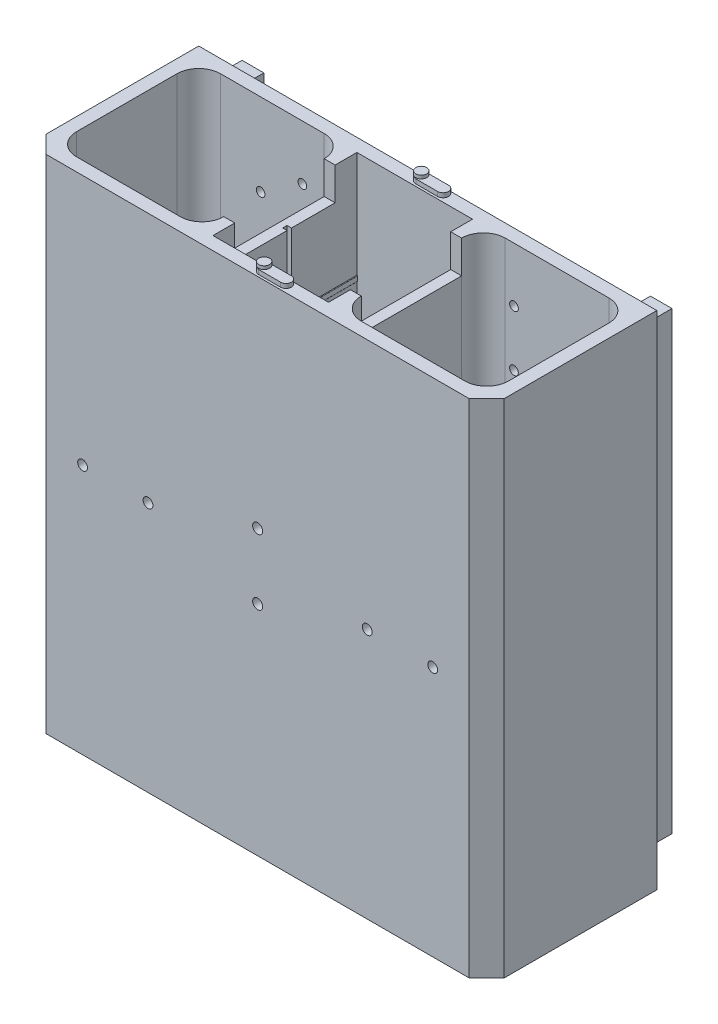
SolidWorks part; units mm, degrees
ref_plane "前视基准面" through (0, 0, 0) normal (0, 0, 1) x (1, 0, 0)
ref_plane "上视基准面" through (0, 0, 0) normal (0, 1, 0) x (1, 0, 0)
ref_plane "右视基准面" through (0, 0, 0) normal (1, 0, 0) x (0, 0, -1)
other "Configuration Table"
sketch "草图1" plane through (0, 0, 0) normal (0, 0, 1) x (1, 0, 0)
  line L1 (0, 0) -> (210, 0)
  line L2 (0, 0) -> (0, 230)
  line L3 (0, 230) -> (210, 230)
  line L4 (210, 0) -> (210, 230)
  line L5 (0, 0) -> (210, 230) construction
  line L6 (0, 230) -> (210, 0) construction
  line L7 (0, 230) -> (26, 230)
  line L8 (0, 230) -> (0, 0)
  line L9 (0, 0) -> (26, 0)
  point P4 (105, 115)
  point P8 (13, 115)
  dimension "D1" = 230
  dimension "D2" = 210
extrude "凸台-拉伸1" add sketch "草图1" along normal blind 6 contours L1 L4 L3 L2
sketch "草图2" plane through (0, 0, 0) normal (0, 0, -1) x (-1, 0, 0)
  line L0 (0, 230) -> (-210, 230) construction
  line L1 (0, 0) -> (-210, 0) construction
  line L2 (-210, 230) -> (-184, 230)
  line L3 (-210, 230) -> (-210, 0)
  line L4 (-210, 0) -> (-184, 0)
  line L5 (-184, 230) -> (-184, 0) construction
  line L6 (-210, 230) -> (-184, 0) construction
  line L7 (-210, 0) -> (-184, 230) construction
  line L9 (0, 230) -> (-20, 230)
  line L10 (0, 230) -> (0, 0)
  line L11 (0, 0) -> (-20, 0)
  line L13 (0, 230) -> (-20, 0) construction
  line L14 (0, 0) -> (-20, 230) construction
  line L15 (-201.925, 219.25) -> (-192.075, 219.25)
  line L16 (-201.925, 219.25) -> (-201.925, 10.75)
  line L17 (-201.925, 10.75) -> (-192.075, 10.75)
  line L18 (-192.075, 219.25) -> (-192.075, 10.75)
  line L19 (-201.925, 219.25) -> (-192.075, 10.75) construction
  line L20 (-201.925, 10.75) -> (-192.075, 219.25) construction
  line L21 (-14.85, 219.25) -> (-4.85, 219.25)
  line L22 (-14.85, 219.25) -> (-14.85, 10.75)
  line L23 (-14.85, 10.75) -> (-4.85, 10.75)
  line L24 (-4.85, 219.25) -> (-4.85, 10.75)
  line L25 (-14.85, 219.25) -> (-4.85, 10.75) construction
  line L26 (-14.85, 10.75) -> (-4.85, 219.25) construction
  point P6 (-197, 115)
  point P18 (-197, 115)
  point P23 (-9.85, 115)
  dimension "D1" = 26
  dimension "D2" = 20
  dimension "D3" = 208.5
  dimension "D4" = 9.85
  dimension "D5" = 13
  dimension "D6" = 115
  dimension "D7" = 208.5
  dimension "D8" = 115
  dimension "D9" = 9.85
  dimension "D10" = 10
extrude "凸台-拉伸3" add sketch "草图2" along normal blind 15 contours L18 L15 L16 L17 | L24 L21 L22 L23
sketch "草图3" plane through (0, 0, 0) normal (0, 0, -1) x (-1, 0, 0)
  line L0 (0, 0) -> (-210, 0) construction
  line L1 (-210, 230) -> (-184, 230)
  line L2 (-210, 230) -> (-210, 0)
  line L3 (-210, 0) -> (-184, 0)
  line L4 (-184, 230) -> (-184, 0)
  line L5 (-210, 230) -> (-184, 0) construction
  line L6 (-210, 0) -> (-184, 230) construction
  line L7 (-210, 115) -> (119.2636, 115) construction
  line L8 (0, 230) -> (-20, 230)
  line L9 (0, 230) -> (0, 0)
  line L10 (0, 0) -> (-20, 0)
  line L11 (-20, 230) -> (-20, 0)
  line L12 (0, 230) -> (-20, 0) construction
  line L13 (0, 0) -> (-20, 230) construction
  line L14 (-105, 230) -> (-105, 0) construction
  circle A0 centre (-169.6426, 192.25) radius 2
  circle A1 centre (-150.5, 205) radius 2
  circle A2 centre (-150.5, 179.5) radius 2
  circle A3 centre (-150.5, 50.5) radius 2
  circle A4 centre (-150.5, 25) radius 2
  circle A5 centre (-169.6426, 37.75) radius 2
  circle A6 centre (-34.3574, 192.25) radius 2
  circle A7 centre (-53.5, 205) radius 2
  circle A8 centre (-53.5, 179.5) radius 2
  circle A9 centre (-53.5, 50.5) radius 2
  circle A10 centre (-53.5, 25) radius 2
  circle A11 centre (-34.3574, 37.75) radius 2
  point P4 (-197, 115)
  point P12 (-10, 115)
  dimension "D8" = 4
  dimension "D9" = 4
  dimension "D10" = 4
  dimension "D12" = 4
  dimension "D13" = 4
  dimension "D14" = 4
  dimension "D1" = 26
  dimension "D2" = 20
  dimension "D3" = 25.5
  dimension "D4" = 23
  dimension "D5" = 23
  dimension "D6" = 33.5
  dimension "D7" = 33.5
  dimension "D11" = 90
  dimension "D15" = 25.5
  dimension "D16" = 23
  dimension "D17" = 23
  dimension "D18" = 33.5
  dimension "D19" = 33.5
  dimension "D20" = 90
extrude "切除-拉伸1" cut sketch "草图3" against normal blind 10 contours A10 | A11 | A9 | A6 | A8 | A7 | A1 | A2 | A0 | A4 | A3 | A5
chamfer "倒角1" [suppressed] distance 10 angle 45
sketch "草图5" [suppressed] plane through (0, 0, 0) normal (0, 0, -1) x (-1, 0, 0)
  line L0 (-172.5, 115) -> (-135, 115) construction
  line L1 (-10, 230) -> (-200, 230) construction
  line L2 (-210, 10) -> (-210, 220) construction
  line L5 (-210, 220) -> (-210, 0)
  line L8 (-75, 115) -> (-37.5, 115) construction
  line L9 (-210, 0) -> (-184, 220) construction
  line L10 (0, 10) -> (0, 220) construction
  circle A0 centre (-172.5, 115) radius 2.5
  circle A1 centre (-135, 115) radius 2.5
  circle A2 centre (-75, 115) radius 2.5
  circle A3 centre (-37.5, 115) radius 2.5
  point P12 (-197, 110)
  dimension "D3" = 5
  dimension "D4" = 5
  dimension "D8" = 5
  dimension "D9" = 5
  dimension "D1" = 37.5
  dimension "D2" = 115
  dimension "D5" = 75
  dimension "D6" = 26
  dimension "D7" = 37.5
  dimension "D10" = 115
  dimension "D11" = 75
extrude "切除-拉伸2" [suppressed] cut sketch "草图5" against normal blind 10 contours A0 | A1 | A3 | A2
sketch "草图6" plane through (0, 0, 6) normal (0, 0, 1) x (1, 0, 0)
  line L0 (105, 230) -> (105, 0) construction
  line L3 (0, 115) -> (210, 115) construction
  line L6 (86.25, 115) -> (123.75, 115) construction
  line L7 (105, 133.75) -> (105, 96.25) construction
  circle A2 centre (105, 133.75) radius 2.5
  circle A3 centre (105, 96.25) radius 2.5
  point P7 (105, 115)
  point P11 (105, 115)
  dimension "D1" = 37.5
  dimension "D2" = 5
  dimension "D3" = 5
extrude "切除-拉伸3" [suppressed] cut sketch "草图6" against normal blind 10
sketch "草图7" [suppressed] plane through (0, 0, 18) normal (0, 0, 1) x (1, 0, 0)
  line L0 (0, 0) -> (210, 0) construction
  line L1 (0, 230) -> (6, 230)
  line L2 (0, 230) -> (0, 0)
  line L3 (0, 0) -> (6, 0)
  line L4 (6, 230) -> (6, 0)
  line L5 (0, 230) -> (6, 0) construction
  line L6 (0, 0) -> (6, 230) construction
  point P4 (3, 115)
  dimension "D1" = 6
extrude "凸台-拉伸4" [suppressed] add sketch "草图7" along normal blind 55
sketch "草图8" [suppressed] plane through (0, 0, 18) normal (0, 0, 1) x (1, 0, 0)
  line L0 (0, 0) -> (210, 0) construction
  line L1 (210, 230) -> (200.2731, 230)
  line L2 (210, 230) -> (210, 0)
  line L3 (210, 0) -> (200.2731, 0)
  line L4 (200.2731, 230) -> (200.2731, 0)
  line L5 (210, 230) -> (200.2731, 0) construction
  line L6 (210, 0) -> (200.2731, 230) construction
  point P4 (205.1365, 115)
  dimension "D1" = 9.7269
sketch "草图17" plane through (0, 0, 6) normal (0, 0, 1) x (1, 0, 0)
  line L0 (0, 0) -> (210, 0) construction
  line L1 (0, 230) -> (6, 230)
  line L2 (0, 230) -> (0, 0)
  line L3 (0, 0) -> (6, 0)
  line L4 (6, 230) -> (6, 0)
  line L5 (0, 230) -> (6, 0) construction
  line L6 (0, 0) -> (6, 230) construction
  line L8 (210, 230) -> (204, 230)
  line L9 (210, 230) -> (210, 0)
  line L10 (210, 0) -> (204, 0)
  line L11 (204, 230) -> (204, 0)
  line L12 (210, 230) -> (204, 0) construction
  line L13 (210, 0) -> (204, 230) construction
  point P4 (3, 115)
  point P12 (207, 115)
  dimension "D1" = 6
  dimension "D2" = 6
extrude "凸台-拉伸9" add sketch "草图17" along normal blind 66
ref_plane "基准面2" through (0, 0, 72) normal (0, 0, 1) x (1, 0, 0)
sketch "草图18" plane through (0, 0, 72) normal (0, 0, 1) x (1, 0, 0)
  line L0 (210, 230) -> (204, 230) construction
  line L1 (210, 0) -> (210, 230) construction
  line L2 (204, 0) -> (210, 0) construction
  line L3 (6, 0) -> (204, 0) construction
  line L4 (0, 0) -> (6, 0) construction
  line L5 (0, 230) -> (0, 0) construction
  line L6 (6, 230) -> (0, 230) construction
  line L7 (6, 230) -> (204, 230) construction
  line L8 (210, 230) -> (204, 230)
  line L9 (210, 0) -> (210, 230)
  line L10 (204, 0) -> (210, 0)
  line L11 (6, 0) -> (204, 0)
  line L12 (0, 0) -> (6, 0)
  line L13 (0, 230) -> (0, 0)
  line L14 (6, 230) -> (0, 230)
  line L15 (6, 230) -> (204, 230)
extrude "凸台-拉伸10" add sketch "草图18" along normal blind 6
chamfer "倒角3" distance 8 angle 45 2 edges at (0, 115, 78) (210, 115, 78)
sketch "草图19" plane through (0, 0, 72) normal (0, 0, -1) x (-1, 0, 0)
  line L0 (-105, 230) -> (-105, 0) construction
  line L2 (-131.5, 230) -> (-136.5, 230)
  line L3 (0, 230) -> (-210, 230) construction
  line L4 (0, 0) -> (-210, 0) construction
  line L5 (-131.5, 230) -> (-131.5, 0)
  line L6 (-131.5, 230) -> (-78.5, 230)
  line L7 (-131.5, 230) -> (-131.5, 0)
  line L8 (-131.5, 0) -> (-78.5, 0)
  line L9 (-78.5, 230) -> (-78.5, 0)
  line L10 (-131.5, 230) -> (-78.5, 0) construction
  line L11 (-131.5, 0) -> (-78.5, 230) construction
  line L12 (-131.5, 0) -> (-136.5, 0)
  line L13 (-136.5, 230) -> (-136.5, 0)
  line L14 (-131.5, 230) -> (-136.5, 0) construction
  line L15 (-131.5, 0) -> (-136.5, 230) construction
  line L16 (-78.5, 230) -> (-73.5, 230)
  line L17 (-78.5, 230) -> (-78.5, 0)
  line L18 (-78.5, 0) -> (-73.5, 0)
  line L19 (-73.5, 230) -> (-73.5, 0)
  line L20 (-78.5, 230) -> (-73.5, 0) construction
  line L21 (-78.5, 0) -> (-73.5, 230) construction
  point P10 (-105, 115)
  point P13 (-134, 115)
  point P16 (-76, 115)
  dimension "D1" = 53
  dimension "D2" = 0
  dimension "D3" = 5
  dimension "D4" = 5
extrude "凸台-拉伸11" add sketch "草图19" along normal blind 66 contours L19 L7 L9 L4 | L7 L13 L4 L5
fillet "圆角4" radius 10 8 edges at (136.5, 115, 72) (136.5, 115, 6) (204, 115, 6) (204, 115, 72) (73.5, 115, 6) (73.5, 115, 72) (6, 115, 6) (6, 115, 72)
sketch "草图21" plane through (0, 0, 72) normal (0, 0, 1) x (1, 0, 0)
  line L0 (8, 115) -> (202, 115) construction
  line L1 (8, 230) -> (8, 0) construction
  line L2 (202, 0) -> (202, 230) construction
  line L3 (105, 230) -> (105, 0) construction
  line L4 (202, 230) -> (8, 230) construction
  line L5 (8, 0) -> (202, 0) construction
  line L6 (105, 130) -> (105, 100) construction
  circle A0 centre (105, 130) radius 2.3
  circle A1 centre (105, 100) radius 2.3
  point P14 (105, 115)
  dimension "D3" = 4.6
  dimension "D4" = 4.6
  dimension "D1" = 0
  dimension "D2" = 30
extrude "切除-拉伸9" cut sketch "草图21" along normal blind 6 contours A1 | A0
sketch "草图23" plane through (78.5, 0, 0) normal (1, 0, 0) x (0, 0, -1)
  line L0 (-6, 80) -> (-70, 80)
  line L1 (-6, 230) -> (-70, 230) construction
  line L2 (-6, 230) -> (-6, 0) construction
  line L3 (-6, 0) -> (-70, 0) construction
  line L4 (-70, 230) -> (-70, 0) construction
  line L5 (-6, 230) -> (-70, 0) construction
  line L6 (-6, 0) -> (-70, 230) construction
  line L7 (-6, 230) -> (-70, 230)
  line L8 (-6, 230) -> (-6, 40)
  line L9 (-6, 40) -> (-70, 40)
  line L10 (-70, 230) -> (-70, 40)
  line L11 (-6, 230) -> (-70, 40) construction
  line L12 (-6, 40) -> (-70, 230) construction
  point P4 (-38, 115)
  point P9 (-38, 135)
  dimension "D1" = 190
  dimension "D2" = 40
sketch "草图24" plane through (0, 0, 6) normal (0, 0, 1) x (1, 0, 0)
  line L0 (78.5, 80.5) -> (78.5, 79.5) construction
  line L1 (78.5, 230) -> (78.5, 40) construction
  line L2 (80, 80.5) -> (80, 79.5)
  line L4 (78.5, 82) -> (78.5, 78)
  arc A0 (80, 80.5) -> (78.5, 82) centre (78.5, 80.5) ccw
  arc A1 (78.5, 78) -> (80, 79.5) centre (78.5, 79.5) ccw
  point P0 (78.5, 80)
  point P6 (78.5, 80)
  dimension "D3" = 1.5
  dimension "D4" = 1.5
  dimension "D1" = 0
  dimension "D2" = 1
extrude "凸台-拉伸12" [suppressed] add sketch "草图24" along normal blind 66
ref_plane "基准面3" through (105, 0, 0) normal (-1, 0, 0) x (0, 0, 1)
mirror "镜向1" [suppressed] about plane through (105, 0, 0) normal (-1, 0, 0)
sketch "草图25" plane through (0, 0, 72) normal (0, 0, -1) x (-1, 0, 0)
  line L8 (-131.5, 230) -> (-131.5, 0)
  line L11 (-131.5, 0) -> (-78.5, 0)
  line L12 (-78.5, 0) -> (-78.5, 230)
  line L15 (-78.5, 230) -> (-131.5, 230)
  line L16 (-131.5, 230) -> (-131.5, 0)
  line L19 (-131.5, 0) -> (-78.5, 0)
  line L20 (-78.5, 0) -> (-78.5, 230)
  line L23 (-78.5, 230) -> (-131.5, 230)
  dimension "D1" = 0
sketch "草图26" plane through (0, 0, 72) normal (0, 0, -1) x (-1, 0, 0)
  line L0 (-131.5, 181) -> (-131.5, 179) construction
  line L1 (-131.5, 230) -> (-131.5, 0) construction
  line L2 (-131.26, 181) -> (-131.26, 179)
  line L3 (-131.74, 181) -> (-131.74, 179)
  line L4 (-78.5, 230) -> (-131.5, 230) construction
  line L5 (-131.5, 230) -> (-131.5, 0) construction
  line L6 (-78.5, 230) -> (-131.5, 230) construction
  line L7 (-131.5, 22.5) -> (-131.5, 20.5) construction
  line L8 (-131.26, 22.5) -> (-131.26, 20.5)
  line L9 (-131.74, 22.5) -> (-131.74, 20.5)
  arc A0 (-131.26, 181) -> (-131.74, 181) centre (-131.5, 181) ccw
  arc A1 (-131.74, 179) -> (-131.26, 179) centre (-131.5, 179) ccw
  arc A2 (-131.26, 22.5) -> (-131.74, 22.5) centre (-131.5, 22.5) ccw
  arc A3 (-131.74, 20.5) -> (-131.26, 20.5) centre (-131.5, 20.5) ccw
  point P4 (-131.5, 180)
  point P14 (-131.5, 21.5)
  dimension "D1" = 0.24
  dimension "D2" = 2
  dimension "D3" = 50
  dimension "D4" = 2
extrude "凸台-拉伸13" add sketch "草图26" along normal blind 66
mirror "镜向2" about plane through (105, 0, 0) normal (-1, 0, 0) of "凸台-拉伸13"
sketch "草图28" plane through (0, 0, 72) normal (0, 0, -1) x (-1, 0, 0)
  line L0 (-78.5, 230) -> (-131.5, 230) construction
  line L1 (-78.5, 230) -> (-131.5, 230) construction
  line L2 (-131.5, 230) -> (-131.5, 0) construction
  line L3 (-131.5, 11.46) -> (-78.5, 11.46)
  line L4 (-131.5, 11.46) -> (-131.5, 8.46)
  line L5 (-131.5, 8.46) -> (-78.5, 8.46)
  line L6 (-78.5, 11.46) -> (-78.5, 8.46)
  line L7 (-131.5, 11.46) -> (-78.5, 8.46) construction
  line L8 (-131.5, 8.46) -> (-78.5, 11.46) construction
  line L9 (-78.5, 230) -> (-78.5, 0) construction
  point P6 (-105, 9.96)
  point P11 (-78.5, 20.2624)
  dimension "D1" = 218.54
  dimension "D2" = 3
extrude "凸台-拉伸14" add sketch "草图28" along normal blind 66
sketch "草图30" plane through (0, 230, 0) normal (0, 1, 0) x (1, 0, 0)
  line L0 (78.5, -6) -> (131.5, -6) construction
  line L1 (78.5, -6) -> (131.5, -6) construction
  line L2 (78.5, -6) -> (78.5, -70) construction
  line L3 (78.5, -36) -> (76.5, -36)
  line L4 (78.5, -36) -> (78.5, -38)
  line L5 (78.5, -38) -> (76.5, -38)
  line L6 (76.5, -36) -> (76.5, -38)
  line L7 (78.5, -36) -> (76.5, -38) construction
  line L8 (78.5, -38) -> (76.5, -36) construction
  point P6 (77.5, -37)
  dimension "D1" = 2
  dimension "D2" = 30
  dimension "D3" = 2
extrude "切除-拉伸10" cut sketch "草图30" against normal blind 35
sketch "草图31" plane through (0, 8.46, 0) normal (0, -1, 0) x (1, 0, 0)
  line L0 (105, 72) -> (105, 6) construction
  line L1 (105, 16.2) -> (117.5, 16.2) construction
  line L2 (98, 23.2) -> (112, 23.2)
  line L3 (98, 23.2) -> (98, 9.2)
  line L4 (131.5, 72) -> (78.5, 72)
  line L5 (78.5, 72) -> (78.5, 6)
  line L6 (78.5, 6) -> (131.5, 6)
  line L7 (131.5, 6) -> (131.5, 72)
  line L8 (131.5, 72) -> (78.5, 72) construction
  line L9 (78.5, 72) -> (78.5, 6) construction
  line L10 (78.5, 6) -> (131.5, 6) construction
  line L11 (131.5, 6) -> (131.5, 72) construction
  line L12 (98, 9.2) -> (112, 9.2)
  line L13 (112, 23.2) -> (112, 9.2)
  line L14 (98, 23.2) -> (112, 9.2) construction
  line L15 (98, 9.2) -> (112, 23.2) construction
  circle A0 centre (92.7, 16.2) radius 1.35
  circle A1 centre (117.3, 16.2) radius 1.35
  point P10 (105, 16.2)
  dimension "D8" = 2.7
  dimension "D9" = 2.7
  dimension "D2" = 14
  dimension "D3" = 14
  dimension "D4" = 12.3
  dimension "D5" = 12.3
  dimension "D6" = 3.2
  dimension "D7" = 0
  dimension "D1" = 0
extrude "切除-拉伸11" cut sketch "草图31" against normal through all
sketch "草图32" plane through (0, 0, 6) normal (0, 0, 1) x (1, 0, 0)
  line L0 (131.5, 8.46) -> (78.5, 8.46) construction
  line L1 (119.5, 8.46) -> (131.5, 8.46)
  line L2 (119.5, 8.46) -> (119.5, -1.54)
  line L3 (119.5, -1.54) -> (131.5, -1.54)
  line L4 (131.5, 8.46) -> (131.5, -1.54)
  line L5 (119.5, 8.46) -> (131.5, -1.54) construction
  line L6 (119.5, -1.54) -> (131.5, 8.46) construction
  line L7 (131.5, 8.46) -> (78.5, 8.46) construction
  line L8 (131.5, 8.46) -> (131.5, 0) construction
  line L9 (131.5, 8.46) -> (131.5, 0) construction
  line L10 (78.5, 0) -> (131.5, 0) construction
  line L11 (78.5, 0) -> (131.5, 0) construction
  point P4 (125.5, 3.46)
  dimension "D1" = 10
  dimension "D2" = 0
  dimension "D3" = 0
  dimension "D4" = 12
extrude "切除-拉伸12" [suppressed] cut sketch "草图32" against normal through all
sketch "草图33" [suppressed] plane through (131.5, 0, 0) normal (-1, 0, 0) x (0, 0, 1)
  line L0 (0, 8.46) -> (72, 8.46) construction
  line L1 (30, 8.46) -> (50, 8.46)
  line L2 (30, 8.46) -> (30, 0)
  line L3 (30, 0) -> (50, 0)
  line L4 (50, 8.46) -> (50, 0)
  line L5 (30, 8.46) -> (50, 0) construction
  line L6 (30, 0) -> (50, 8.46) construction
  line L7 (0, 0) -> (72, 0) construction
  line L8 (0, 0) -> (0, 8.46) construction
  point P4 (40, 4.23)
  point P9 (30, 4.23)
  dimension "D1" = 20
  dimension "D2" = 30
extrude "切除-拉伸13" [suppressed] cut sketch "草图33" against normal up to next
sketch "草图34" plane through (0, 0, 72) normal (0, 0, -1) x (-1, 0, 0)
  line L0 (-170.25, 230) -> (-170.25, 0) construction
  line L1 (-194, 115) -> (-146.5, 115) construction
  line L2 (-185.25, 115) -> (-155.25, 115)
  line L4 (-194, 0) -> (-146.5, 0)
  line L19 (-194, 0) -> (-146.5, 0)
  line L23 (-146.5, 0) -> (-146.5, 230)
  line L25 (-146.5, 0) -> (-146.5, 230)
  line L27 (-146.5, 230) -> (-194, 230)
  line L28 (-146.5, 230) -> (-194, 230)
  line L29 (-194, 230) -> (-194, 0)
  line L30 (-194, 230) -> (-194, 0)
  circle A0 centre (-185.25, 115) radius 2.25
  circle A1 centre (-155.25, 115) radius 2.25
  point P12 (-170.25, 115)
  dimension "D2" = 4.5
  dimension "D3" = 4.5
  dimension "D4" = 30
  dimension "D1" = 0
extrude "切除-拉伸14" cut sketch "草图34" against normal blind 30 contours A0 | A1
sketch "草图36" plane through (0, 0, 72) normal (0, 0, -1) x (-1, 0, 0)
  line L0 (-39.75, 230) -> (-39.75, 0) construction
  line L1 (-63.5, 115) -> (-16, 115) construction
  line L2 (-54.75, 115) -> (-24.75, 115)
  line L4 (-16, 230) -> (-63.5, 230)
  line L19 (-16, 230) -> (-63.5, 230)
  line L23 (-63.5, 230) -> (-63.5, 0)
  line L25 (-63.5, 230) -> (-63.5, 0)
  line L27 (-63.5, 0) -> (-16, 0)
  line L28 (-63.5, 0) -> (-16, 0)
  line L29 (-16, 0) -> (-16, 230)
  line L30 (-16, 0) -> (-16, 230)
  circle A0 centre (-54.75, 115) radius 2.25
  circle A1 centre (-24.75, 115) radius 2.25
  point P12 (-39.75, 115)
  dimension "D2" = 4.5
  dimension "D3" = 4.5
  dimension "D4" = 30
  dimension "D1" = 0
extrude "切除-拉伸15" cut sketch "草图36" against normal blind 30
sketch "草图37" plane through (0, 0, 72) normal (0, 0, -1) x (-1, 0, 0)
  line L12 (-131.5, 11.46) -> (-78.5, 11.46)
  line L13 (-78.5, 11.46) -> (-78.5, 20.26)
  line L14 (-78.74, 20.5) -> (-78.74, 22.5)
  line L15 (-78.5, 22.74) -> (-78.5, 178.76)
  line L16 (-78.74, 179) -> (-78.74, 181)
  line L17 (-78.5, 181.24) -> (-78.5, 230)
  line L18 (-78.5, 230) -> (-131.5, 230)
  line L19 (-131.5, 230) -> (-131.5, 181.24)
  line L20 (-131.26, 181) -> (-131.26, 179)
  line L21 (-131.5, 178.76) -> (-131.5, 22.74)
  line L22 (-131.26, 22.5) -> (-131.26, 20.5)
  line L23 (-131.5, 20.26) -> (-131.5, 11.46)
  line L25 (-78.5, 11.46) -> (-78.5, 20.26)
  line L26 (-78.74, 20.5) -> (-78.74, 22.5)
  line L27 (-78.5, 22.74) -> (-78.5, 178.76)
  line L28 (-78.74, 179) -> (-78.74, 181)
  line L29 (-78.5, 181.24) -> (-78.5, 230)
  line L30 (-78.5, 230) -> (-131.5, 230)
  line L31 (-131.5, 230) -> (-131.5, 181.24)
  line L32 (-131.26, 181) -> (-131.26, 179)
  line L33 (-131.5, 178.76) -> (-131.5, 22.74)
  line L34 (-131.26, 22.5) -> (-131.26, 20.5)
  line L35 (-131.5, 20.26) -> (-131.5, 11.46)
  line L41 (-131.5, 11.46) -> (-78.5, 11.46)
  circle A1 centre (-105, 130) radius 2.3
  circle A2 centre (-105, 130) radius 2.3
  circle A3 centre (-105, 100) radius 2.3
  circle A4 centre (-105, 100) radius 2.3
  arc A8 (-78.74, 20.5) -> (-78.5, 20.26) centre (-78.5, 20.5) ccw
  arc A9 (-78.5, 22.74) -> (-78.74, 22.5) centre (-78.5, 22.5) ccw
  arc A10 (-78.74, 179) -> (-78.5, 178.76) centre (-78.5, 179) ccw
  arc A11 (-78.5, 181.24) -> (-78.74, 181) centre (-78.5, 181) ccw
  arc A12 (-131.26, 181) -> (-131.5, 181.24) centre (-131.5, 181) ccw
  arc A13 (-131.5, 178.76) -> (-131.26, 179) centre (-131.5, 179) ccw
  arc A14 (-131.26, 22.5) -> (-131.5, 22.74) centre (-131.5, 22.5) ccw
  arc A15 (-131.5, 20.26) -> (-131.26, 20.5) centre (-131.5, 20.5) ccw
  arc A16 (-78.74, 20.5) -> (-78.5, 20.26) centre (-78.5, 20.5) ccw
  arc A17 (-78.5, 22.74) -> (-78.74, 22.5) centre (-78.5, 22.5) ccw
  arc A18 (-78.74, 179) -> (-78.5, 178.76) centre (-78.5, 179) ccw
  arc A19 (-78.5, 181.24) -> (-78.74, 181) centre (-78.5, 181) ccw
  arc A20 (-131.26, 181) -> (-131.5, 181.24) centre (-131.5, 181) ccw
  arc A21 (-131.5, 178.76) -> (-131.26, 179) centre (-131.5, 179) ccw
  arc A22 (-131.26, 22.5) -> (-131.5, 22.74) centre (-131.5, 22.5) ccw
  arc A23 (-131.5, 20.26) -> (-131.26, 20.5) centre (-131.5, 20.5) ccw
  dimension "D1" = 0
  dimension "D2" = 0
  dimension "D3" = 0
extrude "凸台-拉伸15" [suppressed] add sketch "草图37" along normal blind 4
sketch "草图39" plane through (73.5, 0, 0) normal (-1, 0, 0) x (0, 0, 1)
  line L1 (16, 230) -> (62, 230)
  line L2 (16, 230) -> (16, 215)
  line L3 (16, 215) -> (62, 215)
  line L4 (62, 230) -> (16, 230)
  line L5 (16, 230) -> (16, 0)
  line L6 (16, 0) -> (62, 0)
  line L7 (16, 230) -> (16, 0)
  line L8 (62, 230) -> (16, 230)
  line L10 (16, 0) -> (62, 0)
  line L12 (62, 230) -> (62, 215)
  line L13 (16, 230) -> (62, 215) construction
  line L14 (16, 215) -> (62, 230) construction
  line L18 (62, 0) -> (62, 230)
  line L19 (62, 0) -> (62, 230)
  point P6 (39, 222.5)
  line M6 (62, 230) -> (16, 230)
  line M7 (16, 230) -> (16, 0)
  line M9 (62, 0) -> (62, 230)
  dimension "D2" = 15
  dimension "D1" = 0
extrude "切除-拉伸16" cut sketch "草图39" against normal blind 104 contours L3 M7 M9 M6
sketch "草图40" plane through (0, 230, 0) normal (0, 1, 0) x (1, 0, 0)
  line L0 (105, 0) -> (105, -6) construction
  line L1 (0, 0) -> (210, 0) construction
  line L2 (78.5, -6) -> (131.5, -6) construction
  circle A0 centre (105, -3) radius 1.5
  dimension "D1" = 3
extrude "凸台-拉伸16" add sketch "草图40" along normal blind 3
sketch "草图41" plane through (0, 233, 0) normal (0, 1, 0) x (1, 0, 0)
  circle A0 centre (105, -3) radius 2.5
  dimension "D1" = 5
extrude "凸台-拉伸17" add sketch "草图41" along normal blind 1.5
sketch "草图42" plane through (0, 230, 0) normal (0, 1, 0) x (1, 0, 0)
  line L6 (0, 0) -> (0, -70)
  line L7 (0, -70) -> (8, -78)
  line L8 (8, -78) -> (202, -78)
  line L9 (202, -78) -> (210, -70)
  line L10 (210, -70) -> (210, 0)
  line L11 (210, 0) -> (0, 0)
  line L12 (0, 0) -> (0, -70)
  line L13 (0, -70) -> (8, -78)
  line L14 (8, -78) -> (202, -78)
  line L15 (202, -78) -> (210, -70)
  line L16 (210, -70) -> (210, 0)
  line L17 (210, 0) -> (0, 0)
  circle A0 centre (105, -3) radius 1.6
  circle A1 centre (105, -3) radius 1.5
  circle A2 centre (105, -3) radius 1.5 construction
  dimension "D3" = 3.2
  dimension "D1" = 0
  dimension "D2" = 0
ref_plane "基准面4" through (0, 230.5, 0) normal (0, 1, 0) x (1, 0, 0)
sketch "草图44" plane through (0, 230.5, 0) normal (0, 1, 0) x (1, 0, 0)
  line L0 (105, -3) -> (115, -3) construction
  line L1 (105, -0.5) -> (115, -0.5)
  line L2 (105, -5.5) -> (115, -5.5)
  arc A2 (105, -0.5) -> (105, -5.5) centre (105, -3) ccw
  arc A3 (115, -5.5) -> (115, -0.5) centre (115, -3) ccw
  circle A4 centre (105, -3) radius 1.62
  point P3 (110, -3)
  dimension "D1" = 2.5
  dimension "D2" = 10
  dimension "D3" = 3.24
extrude "凸台-拉伸19" add sketch "草图44" along normal blind 2 separate body
ref_plane "基准面5" through (0, 0, 39) normal (0, 0, 1) x (1, 0, 0)
mirror "镜向3" about plane through (0, 0, 39) normal (0, 0, 1) of "凸台-拉伸16", "凸台-拉伸17", "凸台-拉伸19"
sketch "草图45" plane through (0, 230, 0) normal (0, 1, 0) x (1, 0, 0)
  line L0 (105, -75) -> (115, -75) construction
  line L1 (105, -72.5) -> (115, -72.5)
  line L2 (105, -77.5) -> (115, -77.5)
  circle A0 centre (105, -75) radius 1.62
  arc A1 (105, -72.5) -> (105, -77.5) centre (105, -75) ccw
  arc A2 (115, -77.5) -> (115, -72.5) centre (115, -75) ccw
  point P3 (110, -75)
  dimension "D1" = 3.24
  dimension "D2" = 2.5
  dimension "D3" = 10
sketch "草图46" plane through (0, 230.5, 0) normal (0, 1, 0) x (1, 0, 0)
  line L2 (115, -72.5) -> (105, -72.5)
  line L3 (105, -77.5) -> (115, -77.5)
  line L4 (115, -72.5) -> (105, -72.5)
  line L5 (105, -77.5) -> (115, -77.5)
  circle A1 centre (105, -75) radius 1.62
  circle A3 centre (105, -75) radius 1.62
  arc A4 (115, -77.5) -> (115, -72.5) centre (115, -75) ccw
  arc A5 (105, -72.5) -> (105, -77.5) centre (105, -75) ccw
  arc A6 (115, -77.5) -> (115, -72.5) centre (115, -75) ccw
  arc A7 (105, -72.5) -> (105, -77.5) centre (105, -75) ccw
  dimension "D1" = 0
  dimension "D2" = 0
extrude "凸台-拉伸20" add sketch "草图46" along normal blind 2 separate body
sketch "草图49" plane through (0, 0, 6) normal (0, 0, 1) x (1, 0, 0)
  line L1 (78.5, 0) -> (90.5, 0)
  line L2 (78.5, 0) -> (78.5, 8.46)
  line L3 (78.5, 8.46) -> (90.5, 8.46)
  line L4 (131.5, 0) -> (131.5, 8.46)
  line L5 (131.5, 8.46) -> (78.5, 8.46)
  line L6 (78.5, 8.46) -> (78.5, 0)
  line L7 (78.5, 0) -> (131.5, 0)
  line L8 (131.5, 0) -> (131.5, 8.46)
  line L9 (131.5, 8.46) -> (78.5, 8.46)
  line L10 (78.5, 8.46) -> (78.5, 0)
  line L11 (78.5, 0) -> (131.5, 0)
  line L12 (90.5, 0) -> (90.5, 8.46)
  line L13 (78.5, 0) -> (90.5, 8.46) construction
  line L14 (78.5, 8.46) -> (90.5, 0) construction
  point P6 (84.5, 4.23)
  line M7 (131.5, 8.46) -> (78.5, 8.46)
  line M8 (78.5, 8.46) -> (78.5, 0)
  line M9 (78.5, 0) -> (131.5, 0)
  dimension "D2" = 12
  dimension "D1" = 0
extrude "切除-拉伸17" cut sketch "草图49" against normal blind 10 contours L12 M9 M7 M8
sketch "草图50" plane through (78.5, 0, 0) normal (1, 0, 0) x (0, 0, -1)
  line L1 (-30, 8.46) -> (-50, 8.46)
  line L2 (-30, 8.46) -> (-30, 0)
  line L3 (-30, 0) -> (-50, 0)
  line L4 (0, 8.46) -> (-72, 8.46)
  line L5 (-72, 8.46) -> (-72, 0)
  line L6 (-72, 0) -> (0, 0)
  line L7 (0, 0) -> (0, 8.46)
  line L8 (0, 8.46) -> (-72, 8.46)
  line L9 (-72, 8.46) -> (-72, 0)
  line L10 (-72, 0) -> (0, 0)
  line L11 (0, 0) -> (0, 8.46)
  line L12 (-50, 8.46) -> (-50, 0)
  line L13 (-30, 8.46) -> (-50, 0) construction
  line L14 (-30, 0) -> (-50, 8.46) construction
  point P8 (-40, 4.23)
  line M7 (0, 8.46) -> (-72, 8.46)
  line M9 (-72, 0) -> (0, 0)
  dimension "D2" = 30
  dimension "D3" = 20
  dimension "D1" = 0
extrude "切除-拉伸18" cut sketch "草图50" against normal blind 10 contours L12 L2 M7 M9
